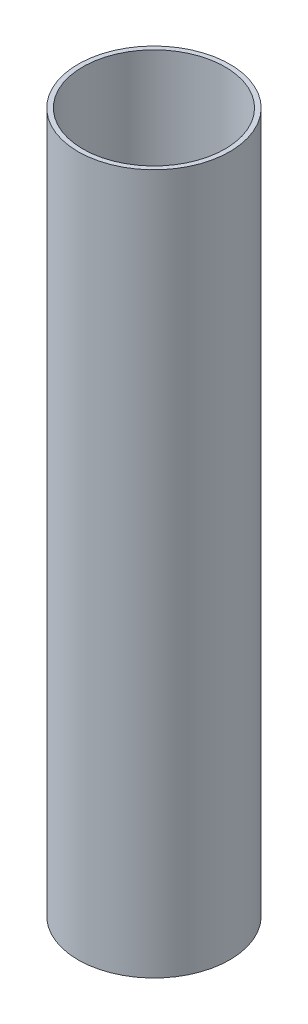
SolidWorks part; units mm, degrees
material "7075-T6 (SN)"
ref_plane "Front Plane" through (0, 0, 0) normal (0, 0, 1) x (1, 0, 0)
ref_plane "Top Plane" through (0, 0, 0) normal (0, 1, 0) x (1, 0, 0)
ref_plane "Right Plane" through (0, 0, 0) normal (1, 0, 0) x (0, 0, -1)
sketch "Sketch1" plane through (0, 0, 0) normal (0, 1, 0) x (1, 0, 0)
  circle A0 centre (0, 0) radius 30.5
  circle A1 centre (0, 0) radius 32.5
extrude "Boss-Extrude1" add sketch "Sketch1" along normal blind 300
